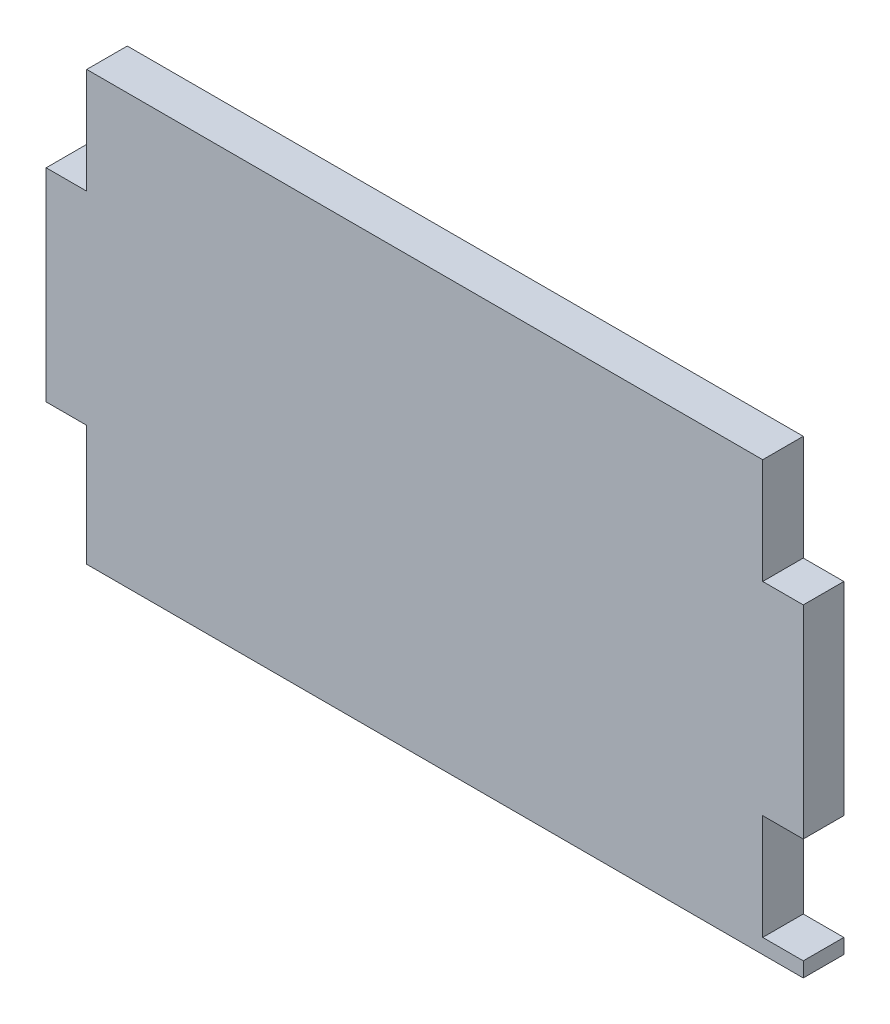
SolidWorks part; units mm, degrees
ref_plane "Front Plane" through (0, 0, 0) normal (0, 0, 1) x (1, 0, 0)
ref_plane "Top Plane" through (0, 0, 0) normal (0, 1, 0) x (1, 0, 0)
ref_plane "Right Plane" through (0, 0, 0) normal (1, 0, 0) x (0, 0, -1)
sketch "Sketch1" plane through (0, 0, 0) normal (0, 0, 1) x (1, 0, 0)
  line L1 (-40.9935, 16.542) -> (15.0065, 16.542)
  line L2 (-40.9935, 16.542) -> (-40.9935, -15.158)
  line L3 (-40.9935, -15.158) -> (15.0065, -15.158)
  line L4 (15.0065, 16.542) -> (15.0065, -15.158)
  dimension "D1" = 31.7
  dimension "D2" = 56
extrude "Boss-Extrude1" add sketch "Sketch1" along normal blind 3
sketch "Sketch2" plane through (0, 0, 3) normal (0, 0, 1) x (1, 0, 0)
  line L12 (-40.9935, 16.542) -> (-37.9935, 16.542)
  line L13 (-40.9935, 16.542) -> (-40.9935, 8.742)
  line L14 (-40.9935, 8.742) -> (-37.9935, 8.742)
  line L15 (-37.9935, 16.542) -> (-37.9935, 8.742)
  dimension "D1" = 7.8
  dimension "D2" = 3
extrude "Cut-Extrude1" cut sketch "Sketch2" against normal through all
pattern_linear "LPattern1" count 2 spacing 22.8 along (0, -1, 0) of "Cut-Extrude1"
sketch "Sketch3" plane through (0, 0, 3) normal (0, 0, 1) x (1, 0, 0)
  line L0 (15.0065, 16.542) -> (-37.9935, 16.542) construction
  line L1 (12.0065, 16.542) -> (15.0065, 16.542)
  line L2 (12.0065, 16.542) -> (12.0065, 8.742)
  line L3 (12.0065, 8.742) -> (15.0065, 8.742)
  line L4 (15.0065, 16.542) -> (15.0065, 8.742)
  line L5 (15.0065, -15.158) -> (15.0065, 16.542) construction
  point P8 (13.5065, 16.542)
  dimension "D1" = 7.8
  dimension "D2" = 3
extrude "Cut-Extrude2" cut sketch "Sketch3" against normal through all
pattern_linear "LPattern2" count 4 spacing 22.8 along (0, -1, 0) of "Cut-Extrude2"
sketch "Sketch6" plane through (0, 0, 3) normal (0, 0, 1) x (1, 0, 0)
  line L0 (-40.9935, -15.158) -> (15.0065, -15.158) construction
  line L1 (-40.9935, -14.058) -> (-37.9935, -14.058)
  line L2 (-40.9935, -14.058) -> (-40.9935, -15.158)
  line L3 (-40.9935, -15.158) -> (-37.9935, -15.158)
  line L4 (-37.9935, -14.058) -> (-37.9935, -15.158)
  dimension "D1" = 3
extrude "Cut-Extrude3" cut sketch "Sketch6" against normal blind 10
